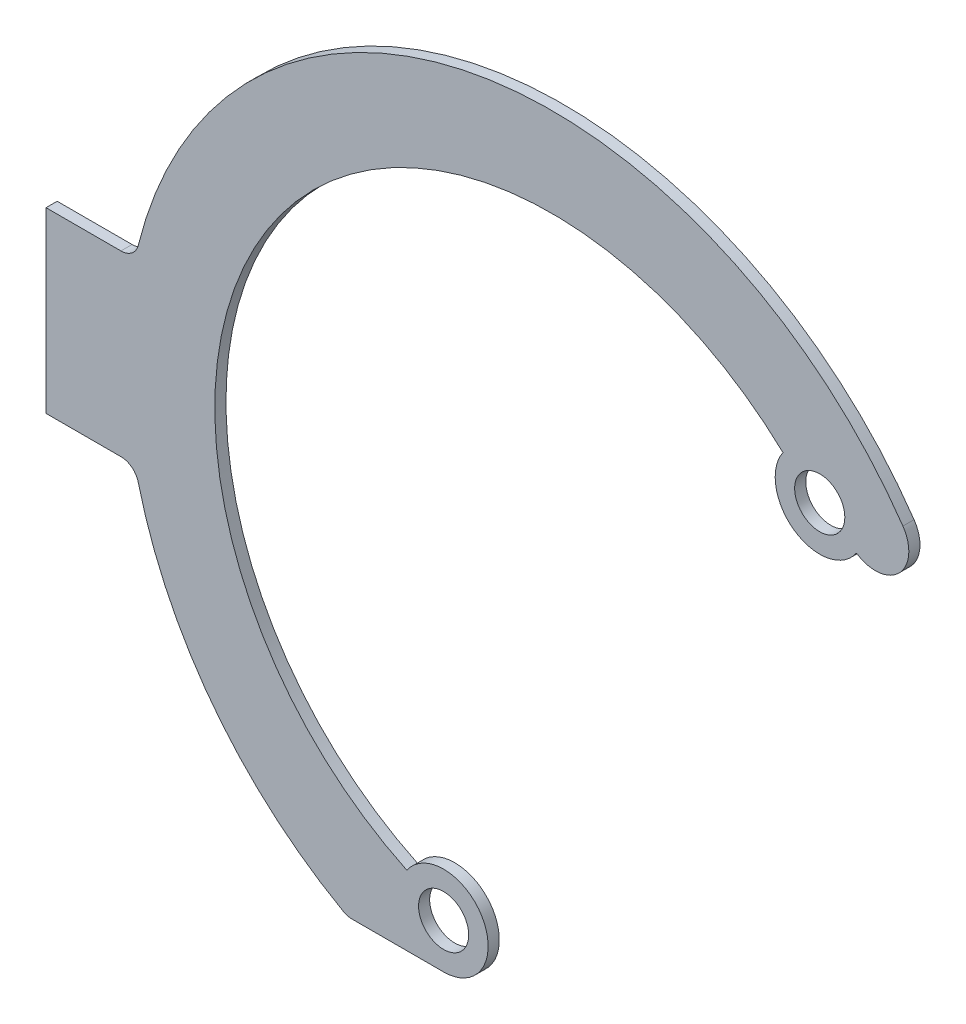
SolidWorks part; units mm, degrees
ref_plane "Front Plane" through (0, 0, 0) normal (0, 0, 1) x (1, 0, 0)
ref_plane "Top Plane" through (0, 0, 0) normal (0, 1, 0) x (1, 0, 0)
ref_plane "Right Plane" through (0, 0, 0) normal (1, 0, 0) x (0, 0, -1)
sketch "Sketch1" plane through (0, 0, 0) normal (0, 0, 1) x (1, 0, 0)
  line L0 (-232.7807, -54.8) -> (49767.2193, -54.8) construction
  line L2 (0, -22.86) -> (0, -27.86) construction
  line L9 (0, 0) -> (107.2279, 156.75) construction
  line L10 (107.2279, 156.75) -> (214.4558, 313.5) construction
  line L11 (34.1342, 206.7512) -> (214.4558, 313.5) construction
  line L12 (107.2279, 156.75) -> (-96.8919, 296.3822) construction
  line L13 (-96.8919, 296.3822) -> (-119.9169, 262.7234) construction
  line L14 (214.4558, 313.5) -> (193.4917, 327.841) construction
  line L15 (214.4558, 313.5) -> (235.42, 299.159) construction
  line L16 (0, -25.4) -> (-54.7876, -25.4)
  line L19 (-226.6927, 238.6522) -> (-175.8927, 238.6522)
  line L20 (-226.6927, 238.6522) -> (-226.6927, 137.0522)
  line L21 (-226.6927, 137.0522) -> (-175.8927, 137.0522)
  line L22 (-175.8927, 238.6522) -> (-175.8927, 137.0522)
  line L23 (-226.6927, 238.6522) -> (-175.8927, 137.0522) construction
  line L24 (-226.6927, 137.0522) -> (-175.8927, 238.6522) construction
  circle A0 centre (0, 0) radius 50.8 construction
  circle A1 centre (214.4558, 313.5) radius 50.8 construction
  arc A3 (-20.9642, 14.341) -> (193.4917, 327.841) centre (61.7615, 187.8522) cw
  circle A5 centre (214.4558, 313.5) radius 14.3002
  circle A6 centre (214.4558, 313.5) radius 25.4
  circle A7 centre (34.1342, 206.7512) radius 158.75 construction
  arc A8 (261.8936, 325.7193) -> (-54.7876, -25.4) centre (61.7615, 187.8522) ccw
  arc A9 (235.42, 299.159) -> (261.8936, 325.7193) centre (246.1879, 314.9) ccw
  circle A10 centre (0, 0) radius 25.4
  circle A11 centre (0, 0) radius 14.3002
  point P36 (-201.2927, 187.8522)
  point P38 (239.0925, 187.8522)
  dimension "D1" = 101.6
  dimension "D10" = 317.5
  dimension "D11" = 28.6004
  dimension "D12" = 50.8
  dimension "D3" = 317.5
  dimension "D5" = 50.8
  dimension "D2" = 4
  dimension "D4" = 22.86
  dimension "D6" = 25
  dimension "D13" = 90
  dimension "D15" = 50.8
  dimension "D16" = 101.6
extrude "Boss-Extrude1" add sketch "Sketch1" along normal blind 6.35 contours L16 A10 A3 A6 A9 A8 | A10 A11 | A6 A5 | A8 L19 L20 L21 | L22 A8
fillet "Fillet1" radius 10.16 3 edges at (-54.7876, -25.4, 3.175) (-175.8927, 137.0522, 3.175) (-175.8927, 238.6522, 3.175)
